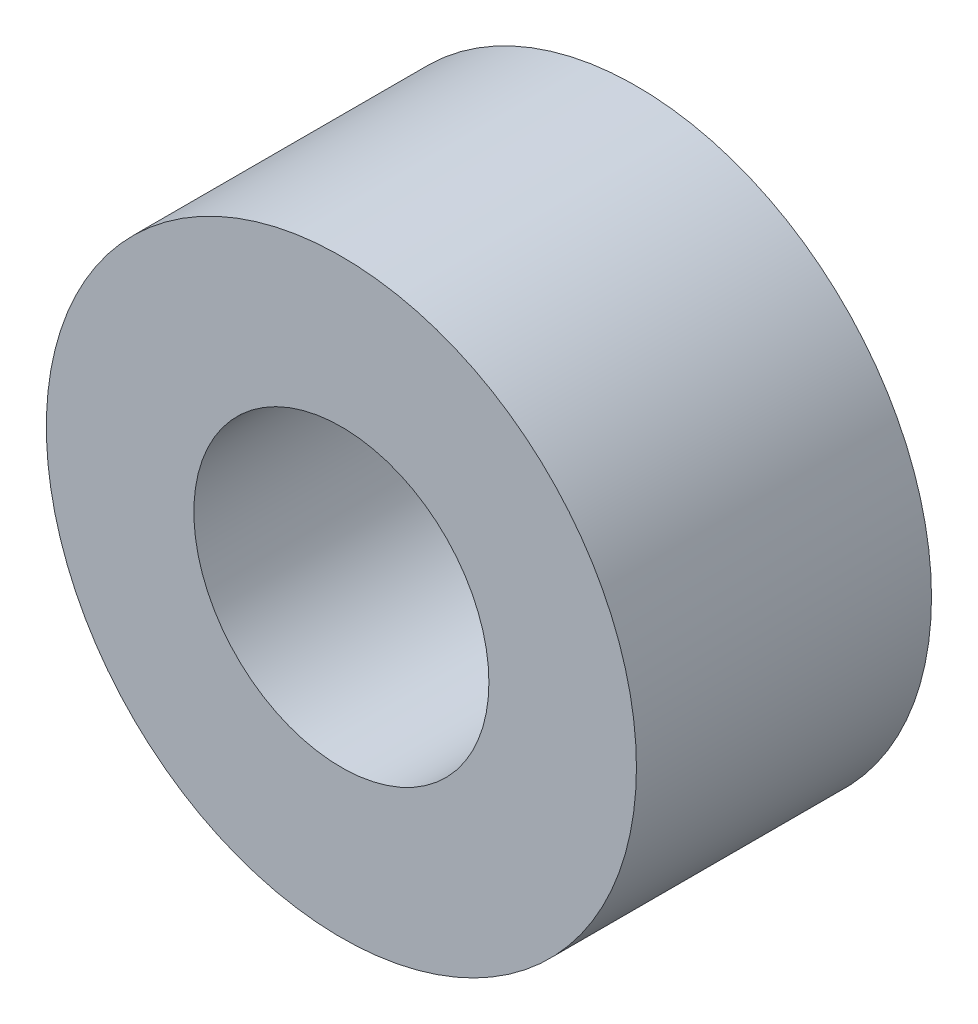
SolidWorks part; units mm, degrees
material "Nylon 101"
ref_plane "Front Plane" through (0, 0, 0) normal (0, 0, 1) x (1, 0, 0)
ref_plane "Top Plane" through (0, 0, 0) normal (0, 1, 0) x (1, 0, 0)
ref_plane "Right Plane" through (0, 0, 0) normal (1, 0, 0) x (0, 0, -1)
sketch "Sketch2" plane through (0, 0, 0) normal (0, 0, 1) x (1, 0, 0)
  circle A0 centre (0, 0) radius 3
  dimension "D1" = 6
extrude "Boss-Extrude1" add sketch "Sketch2" along normal blind 3
sketch "Sketch3" plane through (0, 0, 3) normal (0, 0, 1) x (1, 0, 0)
  circle A0 centre (0, 0) radius 1.5
  dimension "D1" = 3
extrude "Cut-Extrude1" cut sketch "Sketch3" against normal through all
